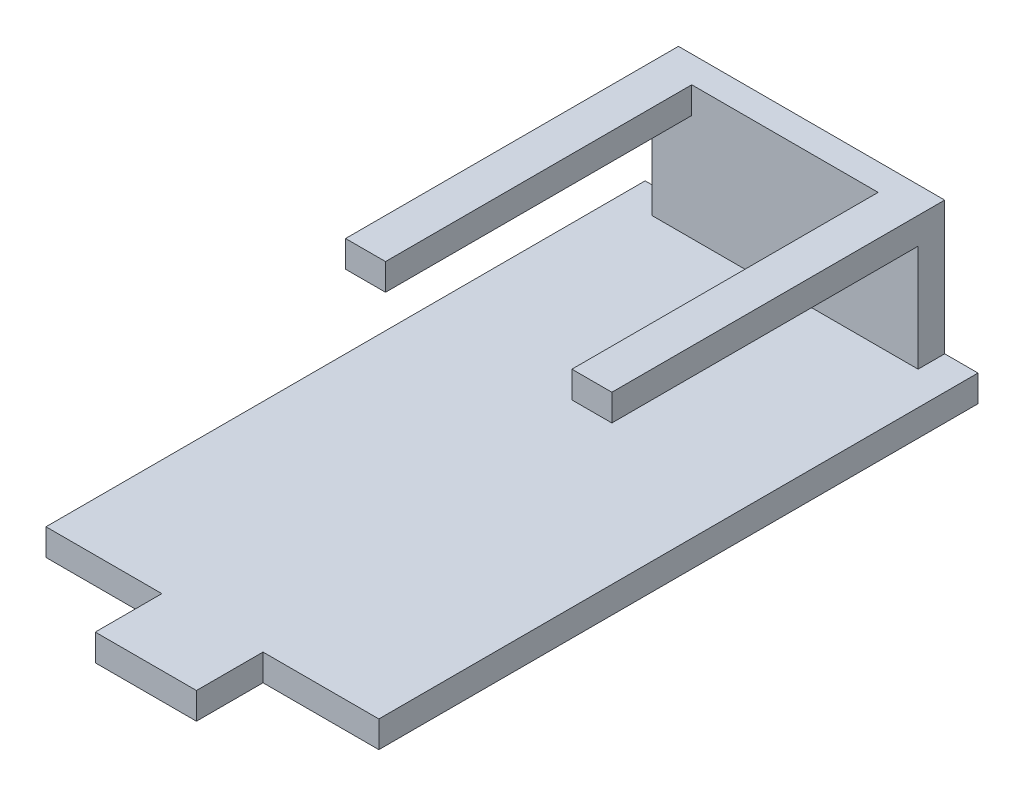
SolidWorks part; units mm, degrees
ref_plane "前视基准面" through (0, 0, 0) normal (0, 0, 1) x (1, 0, 0)
ref_plane "上视基准面" through (0, 0, 0) normal (0, 1, 0) x (1, 0, 0)
ref_plane "右视基准面" through (0, 0, 0) normal (1, 0, 0) x (0, 0, -1)
sketch "草图1" plane through (0, 0, 0) normal (0, 1, 0) x (1, 0, 0)
  line L0 (-27.6263, -29.7092) -> (-2.6263, -29.7092)
  line L1 (-2.6263, -29.7092) -> (-2.6263, 20.2908)
  line L2 (-2.6263, 20.2908) -> (-27.6263, 20.2908)
  line L3 (-27.6263, 20.2908) -> (-27.6263, -29.7092)
extrude "凸台-拉伸1" add sketch "草图1" along normal blind 2
sketch "草图3" plane through (0, 2, 0) normal (0, 1, 0) x (1, 0, 0)
  line L0 (-25.1263, 20.2908) -> (-5.1263, 20.2908)
  line L1 (-5.1263, 20.2908) -> (-5.1263, 18.2908)
  line L2 (-5.1263, 18.2908) -> (-25.1263, 18.2908)
  line L3 (-25.1263, 18.2908) -> (-25.1263, 20.2908)
  line L4 (-2.6263, 20.2908) -> (-27.6263, 20.2908) construction
  point P2 (-15.1263, 20.2908)
  point P7 (-15.1263, 20.2908)
extrude "凸台-拉伸2" add sketch "草图3" along normal blind 10
sketch "草图4" plane through (0, 0, -18.2908) normal (0, 0, 1) x (1, 0, 0)
  line L0 (-25.1263, 10) -> (-5.1263, 10)
  line L1 (-5.1263, 10) -> (-5.1263, 12)
  line L3 (-5.1263, 12) -> (-25.1263, 12)
  line L5 (-25.1263, 12) -> (-25.1263, 10)
  line L6 (-25.1263, 12) -> (-25.1263, 2) construction
  line L7 (-5.1263, 12) -> (-5.1263, 2) construction
  dimension "D1" = 10
extrude "凸台-拉伸3" add sketch "草图4" along normal blind 23
sketch "草图5" plane through (0, 12, 0) normal (0, 1, 0) x (1, 0, 0)
  line L0 (-22.1263, 18.2908) -> (-8.1263, 18.2908)
  line L1 (-8.1263, 18.2908) -> (-8.1263, -4.7092)
  line L2 (-5.1263, -4.7092) -> (-25.1263, -4.7092) construction
  line L3 (-8.1263, -4.7092) -> (-22.1263, -4.7092)
  line L4 (-22.1263, -4.7092) -> (-22.1263, 18.2908)
  line L6 (-25.1263, 20.2908) -> (-25.1263, -4.7092) construction
  line L7 (-5.1263, -4.7092) -> (-5.1263, 20.2908) construction
  line L8 (-5.1263, 20.2908) -> (-25.1263, 20.2908) construction
  dimension "D1" = 3
  dimension "D2" = 3
  dimension "D3" = 2
  dimension "D4" = 14
extrude "切除-拉伸1" cut sketch "草图5" against normal blind 3
sketch "草图6" plane through (0, 0, 29.7092) normal (0, 0, 1) x (1, 0, 0)
  line L2 (-11.3263, 2) -> (-11.3263, 0)
  line L4 (-18.9263, 0) -> (-18.9263, 2)
  line L7 (-18.9263, 2) -> (-27.6263, 2)
  line L8 (-27.6263, 2) -> (-27.6263, 0)
  line L9 (-27.6263, 0) -> (-18.9263, 0)
  line L10 (-11.3263, 2) -> (-2.6263, 2)
  line L11 (-2.6263, 2) -> (-2.6263, 0)
  line L12 (-2.6263, 0) -> (-11.3263, 0)
  point P23 (0, 0)
extrude "切除-拉伸2" cut sketch "草图6" against normal blind 5
